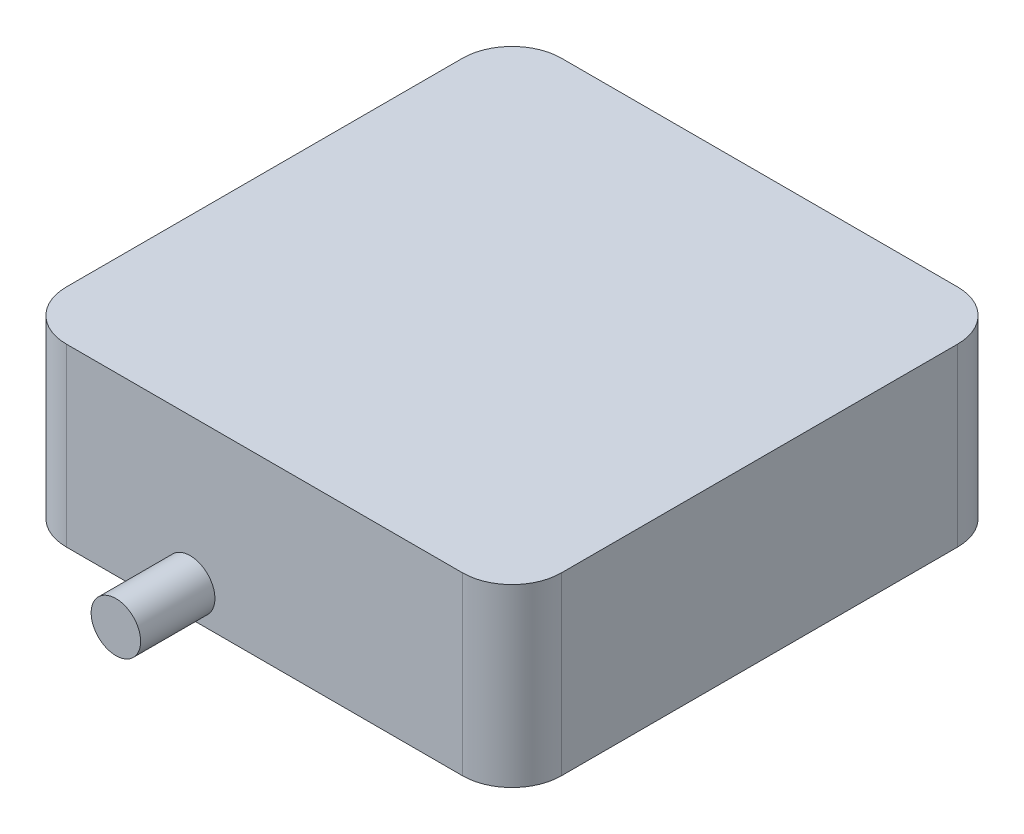
SolidWorks part; units mm, degrees
ref_plane "Front Plane" through (0, 0, 0) normal (0, 0, 1) x (1, 0, 0)
ref_plane "Top Plane" through (0, 0, 0) normal (0, 1, 0) x (1, 0, 0)
ref_plane "Right Plane" through (0, 0, 0) normal (1, 0, 0) x (0, 0, -1)
sketch "Sketch1" plane through (0, 0, 0) normal (0, 1, 0) x (1, 0, 0)
  line L1 (-100, -100) -> (100, -100)
  line L2 (-100, -100) -> (-100, 100)
  line L3 (-100, 100) -> (100, 100)
  line L4 (100, -100) -> (100, 100)
  line L5 (-100, -100) -> (100, 100) construction
  line L6 (-100, 100) -> (100, -100) construction
  point P0 (0, 0)
  dimension "D1" = 200
  dimension "D2" = 200
extrude "Boss-Extrude1" add sketch "Sketch1" along normal blind 71
fillet "Fillet1" radius 20 4 edges at (-100, 35.5, -100) (100, 35.5, -100) (100, 35.5, 100) (-100, 35.5, 100)
sketch "Sketch2" plane through (0, 0, 100) normal (0, 0, 1) x (1, 0, 0)
  line L0 (-30, 71) -> (-30, 0) construction
  line L1 (-80, 71) -> (80, 71) construction
  line L2 (-80, 0) -> (80, 0) construction
  line L3 (-100, 0) -> (-100, 71) construction
  line L4 (-100, 12) -> (100, 12) construction
  line L5 (100, 71) -> (100, 0) construction
  circle A0 centre (-30, 12) radius 10
  point P14 (0, 0)
  dimension "D2" = 20
  dimension "D1" = 70
  dimension "D3" = 12
extrude "Boss-Extrude2" add sketch "Sketch2" along normal blind 30
